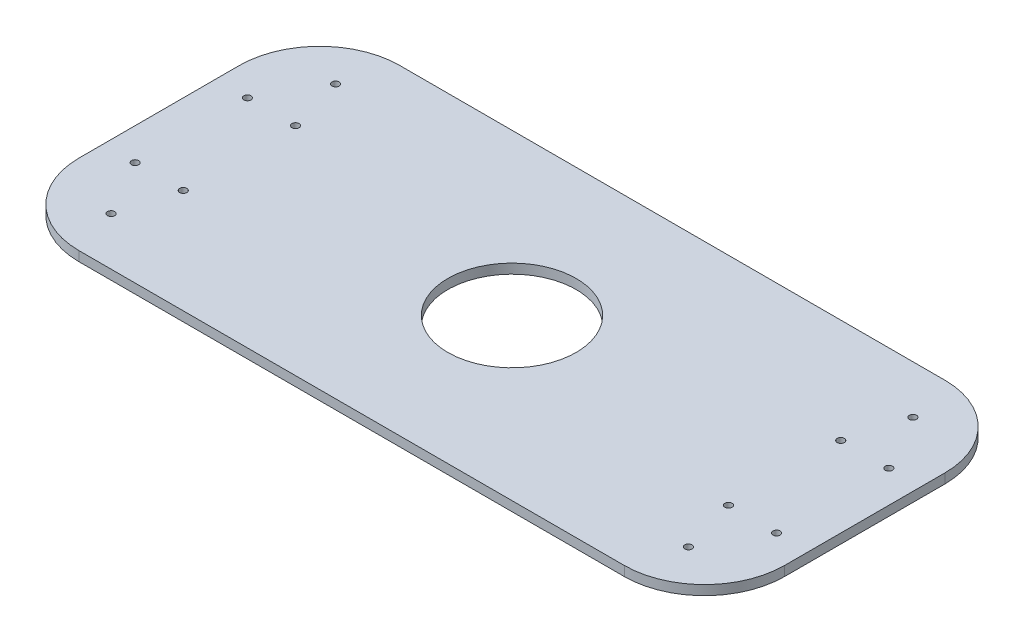
SolidWorks part; units mm, degrees
ref_plane "前视基准面" through (0, 0, 0) normal (0, 0, 1) x (1, 0, 0)
ref_plane "上视基准面" through (0, 0, 0) normal (0, 1, 0) x (1, 0, 0)
ref_plane "右视基准面" through (0, 0, 0) normal (1, 0, 0) x (0, 0, -1)
other "Configuration Table"
sketch "草图6" plane through (0, 0, 0) normal (0, 1, 0) x (1, 0, 0)
  line L0 (0, 0) -> (0, 244.2569) construction
  line L1 (0, 0) -> (293.6379, 0) construction
  line L3 (-220, 100) -> (220, 100)
  line L4 (-220, 100) -> (-220, -100)
  line L5 (-220, -100) -> (220, -100)
  line L6 (220, 100) -> (220, -100)
  circle A0 centre (0, 0) radius 85 construction
  circle A1 centre (0, 0) radius 40
  dimension "D1" = 170
  dimension "D4" = 80
  dimension "D2" = 200
  dimension "D3" = 440
extrude "凸台-拉伸2" add sketch "草图6" along normal blind 6
sketch "草图7" plane through (0, 6, 0) normal (0, 1, 0) x (1, 0, 0)
  line L0 (0, 0) -> (281.8886, 0) construction
  line L1 (-170, 100) -> (170, 100) construction
  line L2 (-220, 50) -> (-220, -50)
  line L3 (-170, -100) -> (170, -100) construction
  line L4 (220, 50) -> (220, -50)
  line L5 (0, 0) -> (0, 132.2554) construction
  line L10 (-220, 100) -> (-220, -100)
  line L11 (-220, -100) -> (220, -100)
  line L12 (220, -100) -> (220, 100)
  line L13 (220, 100) -> (-220, 100)
  line L14 (-220, 100) -> (-220, -100)
  line L15 (-220, -100) -> (220, -100)
  line L16 (220, -100) -> (220, 100)
  line L17 (220, 100) -> (-220, 100)
  arc A0 (-170, -100) -> (-220, -50) centre (-170, -50) cw
  arc A1 (170, -100) -> (220, -50) centre (170, -50) ccw
  arc A2 (220, 50) -> (170, 100) centre (170, 50) ccw
  arc A3 (-170, 100) -> (-220, 50) centre (-170, 50) ccw
  circle A4 centre (170, 35) radius 2.25
  circle A5 centre (200, 35) radius 2.25
  circle A6 centre (180, 70) radius 2.25
  circle A7 centre (-180, 70) radius 2.25
  circle A8 centre (-200, 35) radius 2.25
  circle A9 centre (-170, 35) radius 2.25
  circle A10 centre (-170, -35) radius 2.25
  circle A11 centre (-200, -35) radius 2.25
  circle A12 centre (-180, -70) radius 2.25
  circle A13 centre (180, -70) radius 2.25
  circle A14 centre (200, -35) radius 2.25
  circle A15 centre (170, -35) radius 2.25
  point P10 (-220, -100)
  point P13 (220, -100)
  point P16 (220, 100)
  line M14 (-220, 100) -> (-220, -100)
  line M15 (-220, -100) -> (220, -100)
  line M16 (220, -100) -> (220, 100)
  line M17 (220, 100) -> (-220, 100)
  dimension "D3" = 50
  dimension "D4" = 4.5
  dimension "D1" = 200
  dimension "D2" = 440
  dimension "D5" = 35
  dimension "D6" = 30
  dimension "D7" = 10
  dimension "D8" = 180
  dimension "D9" = 70
  dimension "D10" = 0
extrude "切除-拉伸1" cut sketch "草图7" against normal blind 10 contours A3 A0 L2 M17 M14 M15 | A2 L4 A1 M15 M16 M17 | A8 | A9 | A7 | A6 | A4 | A5 | A0 M15 M14 | A1 M15 M16 | A14 | A15 | A13 | A12 | A10 | A11
